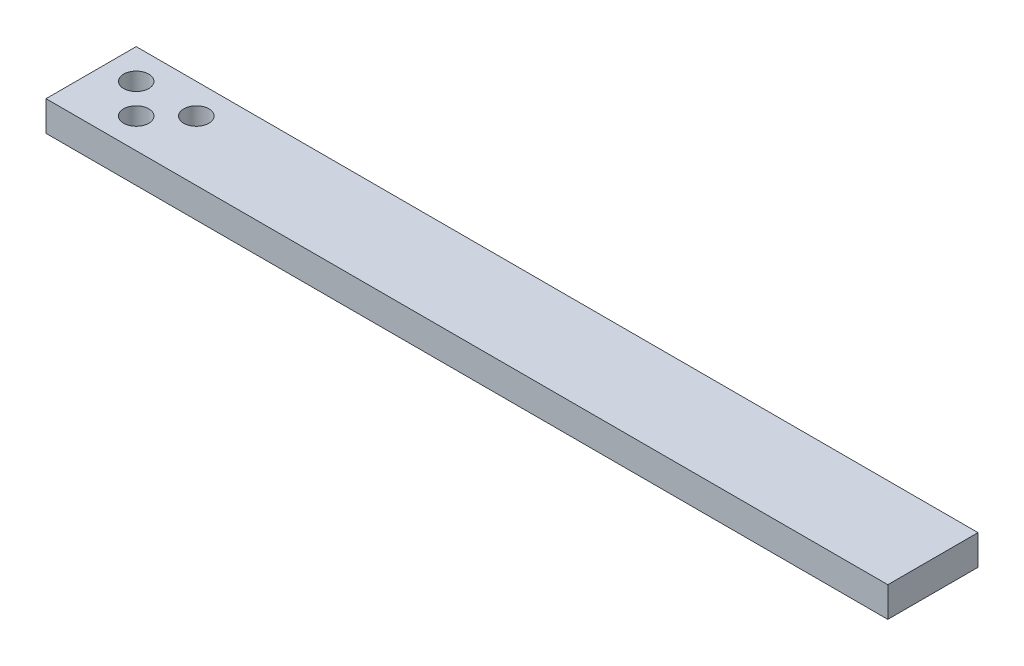
SolidWorks part; units mm, degrees
ref_plane "Front Plane" through (0, 0, 0) normal (0, 0, 1) x (1, 0, 0)
ref_plane "Top Plane" through (0, 0, 0) normal (0, 1, 0) x (1, 0, 0)
ref_plane "Right Plane" through (0, 0, 0) normal (1, 0, 0) x (0, 0, -1)
sketch "Sketch1" plane through (0, 0, 0) normal (0, 1, 0) x (1, 0, 0)
  line L1 (0, 0) -> (177.8, 0)
  line L2 (0, 0) -> (0, 19.05)
  line L3 (0, 19.05) -> (177.8, 19.05)
  line L4 (177.8, 0) -> (177.8, 19.05)
  dimension "D1" = 19.05
  dimension "D2" = 177.8
extrude "Boss-Extrude1" add sketch "Sketch1" along normal blind 6.35
hole_wizard "#4 (0.209) Diameter Hole1" positions "3DSketch1" profile "Sketch2" hole size "#4" standard "ANSI Inch"
sketch3d "3DSketch1"
  line L1 (177.8, 6.35, -19.05) -> (0, 6.35, -19.05) construction
  line L3 (0, 6.35, -19.05) -> (0, 6.35, 0) construction
  circle A4 centre (12.7, 6.35, -12.7) radius 6.35 construction
  point P0 (6.35, 6.35, -12.7)
  point P2 (19.05, 6.35, -12.7)
  point P4 (12.7, 6.35, -6.35)
  point P32 (12.7, 12.7, -12.7)
  point P38 (0, 0, 0)
  dimension "D1" = 12.7
  dimension "D2" = 6.35
  dimension "D3" = 12.7
sketch "Sketch2" plane through (6.35, 6.35, -12.7) normal (1, 0, 0) x (0, 0, 1)
  line L0 (0, 0) -> (0, 12.2629)
  line L1 (0, 12.2629) -> (2.6543, 10.668)
  line L2 (2.6543, 10.668) -> (2.6543, 0)
  line L5 (2.6543, 0) -> (0, 0)
  line L10 (0, 12.2629) -> (-2.6543, 10.668) construction
  line L11 (0, -6.35) -> (0, 107.95) construction
  dimension "Hole Dia." = 5.3086
  dimension "Hole Depth" = 10.668
  dimension "Drill Angle" = 118
